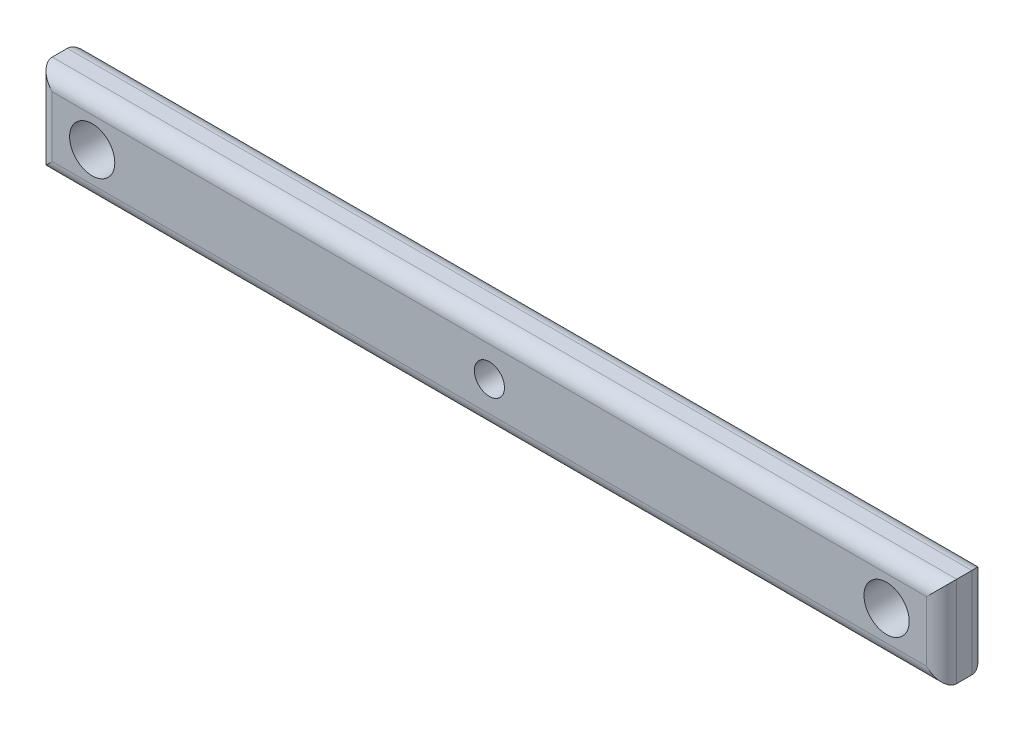
SolidWorks part; units mm, degrees
ref_plane "Alzado" through (0, 0, 0) normal (0, 0, 1) x (1, 0, 0)
ref_plane "Planta" through (0, 0, 0) normal (0, 1, 0) x (1, 0, 0)
ref_plane "Vista lateral" through (0, 0, 0) normal (1, 0, 0) x (0, 0, -1)
sketch "Croquis1" plane through (0, 0, 0) normal (0, 0, 1) x (1, 0, 0)
  line L1 (-30, 3) -> (30, 3)
  line L2 (-30, 3) -> (-30, -3)
  line L3 (-30, -3) -> (30, -3)
  line L4 (30, 3) -> (30, -3)
  point P4 (0, 3)
  point P6 (-30, 0)
  dimension "D1" = 60
  dimension "D2" = 6
extrude "Saliente-Extruir1" add sketch "Croquis1" along normal blind 3
fillet "Redondeo1" radius 1 8 edges at (0, -3, 0) (30, 0, 0) (0, 3, 0) (-30, 0, 0) (0, 3, 3) (30, 0, 3) (0, -3, 3) (-30, 0, 3)
sketch "Croquis2" plane through (0, 0, 3) normal (0, 0, 1) x (1, 0, 0)
  line L0 (29, -2) -> (29, 2) construction
  circle A0 centre (-26.35, 0) radius 1.5
  circle A1 centre (26.35, 0) radius 1.5
  circle A2 centre (0, 0) radius 1
  point P7 (29, 0)
  dimension "D1" = 3
  dimension "D2" = 3
  dimension "D3" = 26.35
  dimension "D5" = 2
  dimension "D4" = 26.35
extrude "Cortar-Extruir1" cut sketch "Croquis2" against normal through all
